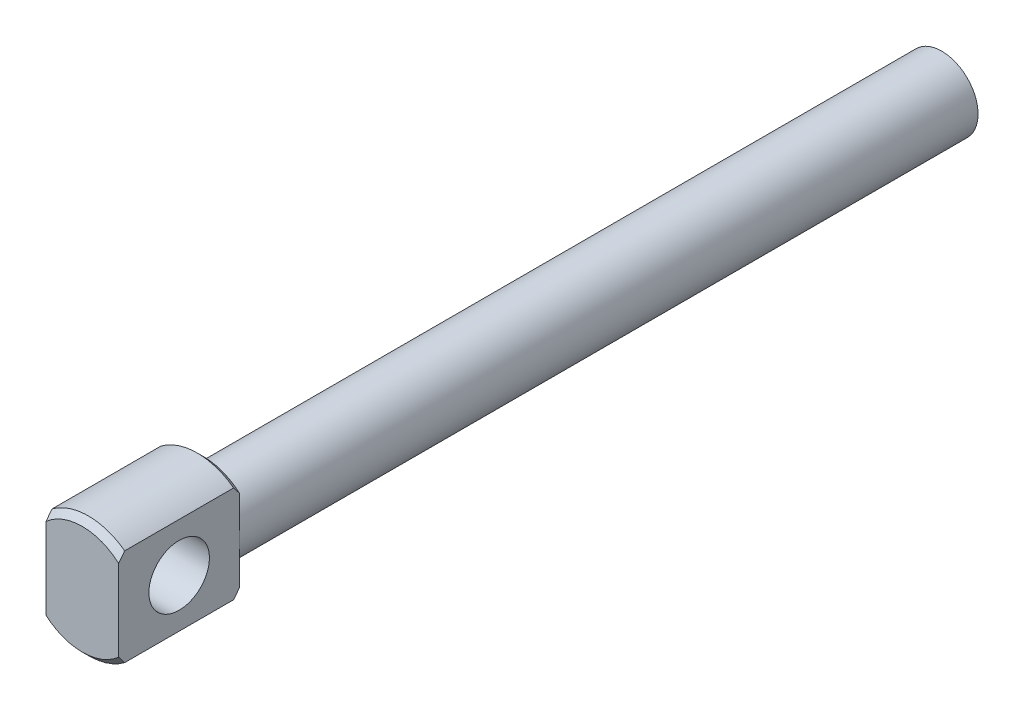
SolidWorks part; units mm, degrees
material "AISI 304"
ref_plane "Front Plane" through (0, 0, 0) normal (0, 0, 1) x (1, 0, 0)
ref_plane "Top Plane" through (0, 0, 0) normal (0, 1, 0) x (1, 0, 0)
ref_plane "Right Plane" through (0, 0, 0) normal (1, 0, 0) x (0, 0, -1)
sketch "Sketch1" plane through (0, 0, 0) normal (0, 0, 1) x (1, 0, 0)
  line L0 (3, 4) -> (3, -4)
  line L1 (-3, 4) -> (-3, -4)
  arc A0 (3, 4) -> (-3, 4) centre (0, 0) ccw
  arc A1 (-3, -4) -> (3, -4) centre (0, 0) ccw
  dimension "D2" = 10
extrude "Boss-Extrude1" add sketch "Sketch1" against normal blind 10
sketch "Sketch2" plane through (0, 0, -10) normal (0, 0, -1) x (-1, 0, 0)
  circle A0 centre (0, 0) radius 3
extrude "Boss-Extrude2" add sketch "Sketch2" along normal blind 61
chamfer "Chamfer1" distance 0.5 angle 45 4 edges at (0, -5, 0) (0, 5, 0) (0, -5, -10) (0, 5, -10)
sketch "Sketch3" plane through (-3, 0, 0) normal (-1, 0, 0) x (0, 0, 1)
  circle A0 centre (-5, 0) radius 2.5
extrude "Cut-Extrude1" cut sketch "Sketch3" against normal blind 61
